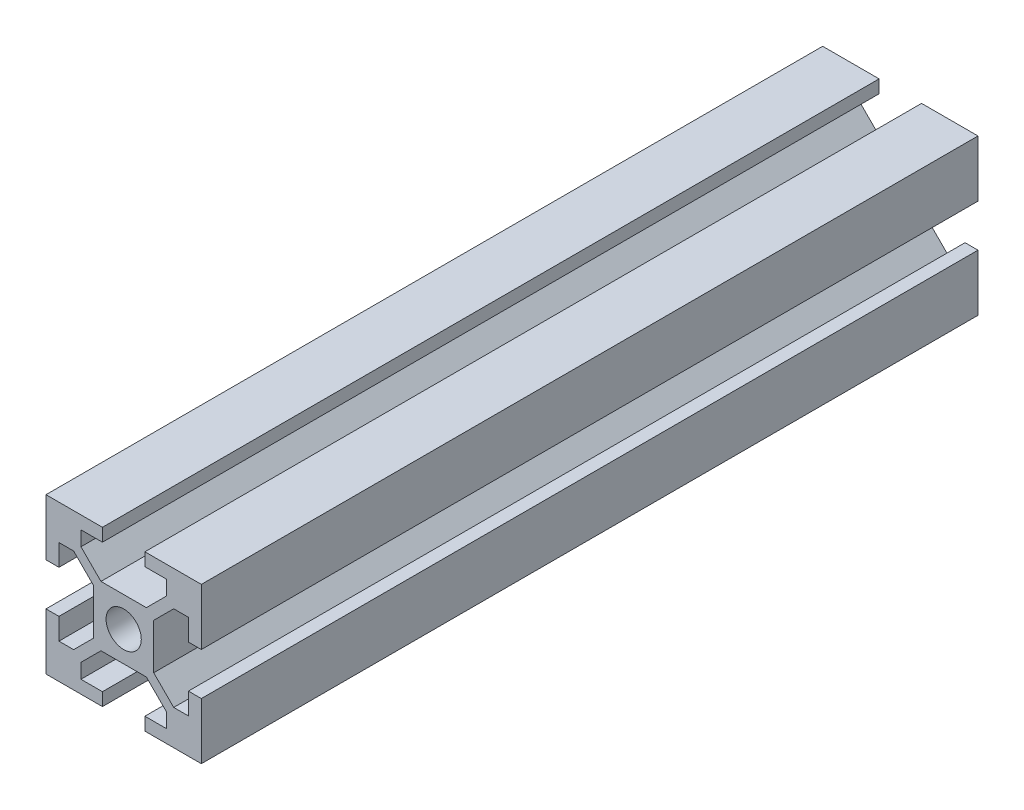
SolidWorks part; units mm, degrees
ref_plane "前视基准面" through (0, 0, 0) normal (0, 0, 1) x (1, 0, 0)
ref_plane "上视基准面" through (0, 0, 0) normal (0, 1, 0) x (1, 0, 0)
ref_plane "右视基准面" through (0, 0, 0) normal (1, 0, 0) x (0, 0, -1)
sketch "草图1" plane through (0, 0, 0) normal (0, 0, 1) x (1, 0, 0)
  line L0 (-4.1, 15) -> (-4.1, 12.5)
  line L1 (-4.3858, -5.8) -> (4.3858, -5.8)
  line L2 (-5.8, -4.3858) -> (-5.8, 4.3858)
  line L3 (-4.3858, 5.8) -> (4.3858, 5.8)
  line L4 (5.8, -4.3858) -> (5.8, 4.3858)
  line L5 (-9.6642, 8.25) -> (-12.5, 8.25)
  line L6 (-8.25, -12.5) -> (-4.1, -12.5)
  line L7 (-15, -15) -> (-4.1, -15)
  line L8 (-15, -15) -> (-15, -4.1)
  line L9 (-8.25, 15) -> (-4.1, 15)
  line L10 (15, -15) -> (15, -4.1)
  line L11 (-8.25, 9.6642) -> (-8.25, 12.5)
  line L12 (-8.25, 15) -> (-15, 15)
  line L13 (9.6642, 8.25) -> (12.5, 8.25)
  line L14 (8.25, 9.6642) -> (8.25, 12.5)
  line L15 (8.25, 15) -> (15, 15)
  line L16 (15, 8.25) -> (15, 15)
  line L17 (9.6642, -8.25) -> (12.5, -8.25)
  line L18 (8.25, -9.6642) -> (8.25, -12.5)
  line L19 (8.25, -15) -> (15, -15)
  line L20 (15, -8.25) -> (15, -15)
  line L21 (-15, 8.25) -> (-15, 15)
  line L22 (-9.6642, -8.25) -> (-12.5, -8.25)
  line L23 (-8.25, -9.6642) -> (-8.25, -12.5)
  line L24 (-8.25, -15) -> (-15, -15)
  line L25 (-15, -8.25) -> (-15, -15)
  line L26 (-12.5, -8.25) -> (-12.5, -4.1)
  line L27 (-8.25, 12.5) -> (-4.1, 12.5)
  line L28 (12.5, -8.25) -> (12.5, -4.1)
  line L29 (-8.25, 9.6642) -> (-4.3858, 5.8)
  line L30 (-9.6642, 8.25) -> (-5.8, 4.3858)
  line L31 (8.25, 9.6642) -> (4.3858, 5.8)
  line L32 (9.6642, 8.25) -> (5.8, 4.3858)
  line L33 (4.3858, -5.8) -> (8.25, -9.6642)
  line L34 (-5.8, -4.3858) -> (-9.6642, -8.25)
  line L35 (4.1, 15) -> (4.1, 12.5)
  line L36 (5.8, -4.3858) -> (9.6642, -8.25)
  line L37 (-4.3858, -5.8) -> (-8.25, -9.6642)
  line L38 (4.1, 15) -> (15, 15)
  line L39 (4.1, 12.5) -> (8.25, 12.5)
  line L40 (-4.1, -12.5) -> (-4.1, -15)
  line L41 (4.1, -15) -> (15, -15)
  line L42 (4.1, -12.5) -> (8.25, -12.5)
  line L43 (4.1, -12.5) -> (4.1, -15)
  line L44 (-15, 4.1) -> (-12.5, 4.1)
  line L45 (-15, -4.1) -> (-12.5, -4.1)
  line L46 (-15, 4.1) -> (-15, 15)
  line L47 (-12.5, 4.1) -> (-12.5, 8.25)
  line L48 (12.5, -4.1) -> (15, -4.1)
  line L49 (12.5, 4.1) -> (15, 4.1)
  line L50 (12.5, 4.1) -> (12.5, 8.25)
  line L51 (15, 4.1) -> (15, 15)
  line L52 (-15, 8.25) -> (-15, 4.1)
  line L53 (15, 8.25) -> (15, 4.1)
  line L54 (8.25, -15) -> (4.1, -15)
  line L55 (8.25, 15) -> (4.1, 15)
  circle A0 centre (0, 0) radius 3.4
extrude "凸台-拉伸1" add sketch "草图1" along normal blind 150 contours L49 L51 L16 L15 L38 L35 L39 L14 L31 L3 L29 L11 L27 L0 L9 L12 L21 L46 L44 L47 L5 L30 L2 L34 L22 L26 L45 L8 L7 L40 L6 L23 L37 L1 L33 L18 L42 L43 L41 L19 L10 L48 L28 L17 L36 L4 L32 L13
